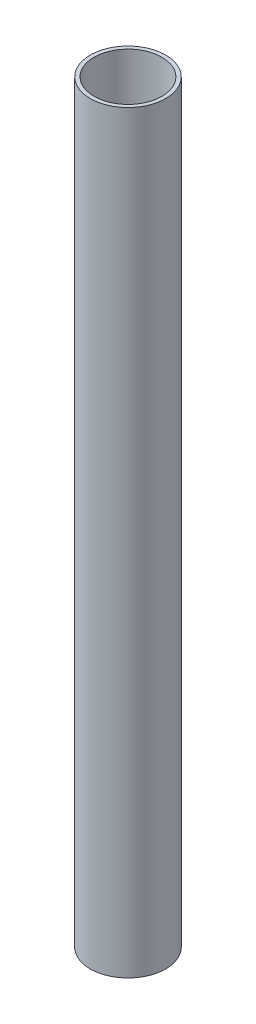
SolidWorks part; units mm, degrees
ref_plane "前视基准面" through (0, 0, 0) normal (0, 0, 1) x (1, 0, 0)
ref_plane "上视基准面" through (0, 0, 0) normal (0, 1, 0) x (1, 0, 0)
ref_plane "右视基准面" through (0, 0, 0) normal (1, 0, 0) x (0, 0, -1)
sketch "草图1" plane through (0, 0, 0) normal (0, 1, 0) x (1, 0, 0)
  circle A0 centre (0, 0) radius 10
  circle A1 centre (0, 0) radius 9
  dimension "D1" = 20
  dimension "D2" = 18
extrude "凸台-拉伸1" add sketch "草图1" along normal blind 200
